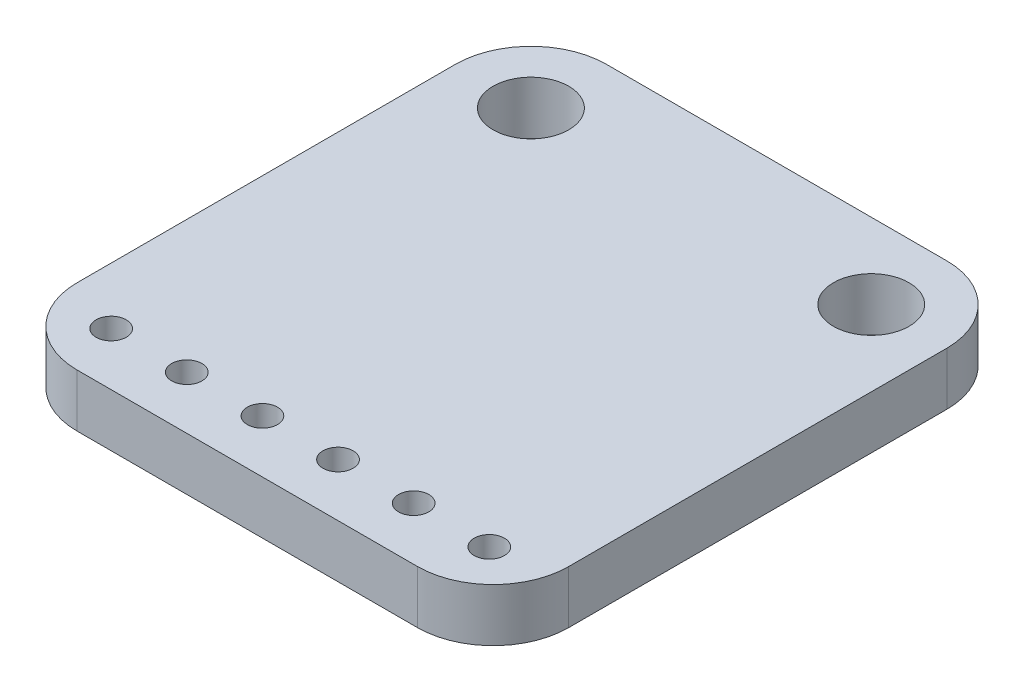
SolidWorks part; units mm, degrees
ref_plane "Front Plane" through (0, 0, 0) normal (0, 0, 1) x (1, 0, 0)
ref_plane "Top Plane" through (0, 0, 0) normal (0, 1, 0) x (1, 0, 0)
ref_plane "Right Plane" through (0, 0, 0) normal (1, 0, 0) x (0, 0, -1)
sketch "Sketch1" plane through (0, 0, 0) normal (0, 1, 0) x (1, 0, 0)
  line L1 (-8.255, 8.89) -> (8.255, 8.89)
  line L2 (-8.255, 8.89) -> (-8.255, -8.89)
  line L3 (-8.255, -8.89) -> (8.255, -8.89)
  line L4 (8.255, 8.89) -> (8.255, -8.89)
  line L5 (-8.255, 8.89) -> (8.255, -8.89) construction
  line L6 (-8.255, -8.89) -> (8.255, 8.89) construction
  point P0 (0, 0)
  dimension "D1" = 16.51
  dimension "D2" = 17.78
extrude "Boss-Extrude1" add sketch "Sketch1" along normal blind 1.778
fillet "Fillet1" radius 2.54 4 edges at (-8.255, 0.889, 8.89) (-8.255, 0.889, -8.89) (8.255, 0.889, -8.89) (8.255, 0.889, 8.89)
sketch "Sketch2" plane through (0, 1.778, 0) normal (0, 1, 0) x (1, 0, 0)
  line L0 (-8.255, -7.112) -> (8.255, -7.112) construction
  line L1 (-8.255, 6.35) -> (-8.255, -6.35) construction
  line L2 (8.255, -6.35) -> (8.255, 6.35) construction
  line L3 (-5.715, -8.89) -> (5.715, -8.89) construction
  circle A0 centre (-6.35, -7.112) radius 0.508
  circle A1 centre (-3.81, -7.112) radius 0.508
  circle A2 centre (-1.27, -7.112) radius 0.508
  circle A3 centre (1.27, -7.112) radius 0.508
  circle A4 centre (3.81, -7.112) radius 0.508
  circle A5 centre (6.35, -7.112) radius 0.508
  dimension "D3" = 1.016
  dimension "D1" = 1.778
  dimension "D2" = 1.905
  dimension "D5" = 1.905
  dimension "D4" = 6
extrude "Cut-Extrude1" cut sketch "Sketch2" against normal up to next
sketch "Sketch4" plane through (0, 0, 0) normal (0, -1, 0) x (-1, 0, 0)
  line L0 (12.1297, 1.27) -> (-13.0317, 1.27) construction
  line L1 (-1.975, 3.245) -> (1.975, 3.245)
  line L2 (-1.975, 3.245) -> (-1.975, -0.705)
  line L3 (-1.975, -0.705) -> (1.975, -0.705)
  line L4 (1.975, 3.245) -> (1.975, -0.705)
  line L5 (0, 10.9348) -> (0, -12.4719) construction
  line L6 (-8.255, -6.35) -> (-8.255, 6.35) construction
  line L7 (8.255, 6.35) -> (8.255, -6.35) construction
  line L8 (-5.715, 8.89) -> (5.715, 8.89) construction
  dimension "D1" = 3.95
  dimension "D2" = 3.95
  dimension "D3" = 7.62
extrude "Boss-Extrude3" add sketch "Sketch4" along normal blind 1.397
sketch "Sketch5" plane through (0, 0, 0) normal (0, -1, 0) x (-1, 0, 0)
  line L0 (-8.255, -6.35) -> (-8.255, 6.35) construction
  line L1 (-5.715, 8.89) -> (5.715, 8.89) construction
  line L2 (8.255, 6.35) -> (8.255, -6.35) construction
  circle A0 centre (-5.715, 6.35) radius 1.27
  circle A1 centre (5.715, 6.35) radius 1.27
  dimension "D1" = 2.54
  dimension "D4" = 2.54
  dimension "D2" = 2.54
  dimension "D3" = 2.54
  dimension "D5" = 2.54
  dimension "D6" = 2.54
extrude "Cut-Extrude2" cut sketch "Sketch5" against normal up to next
